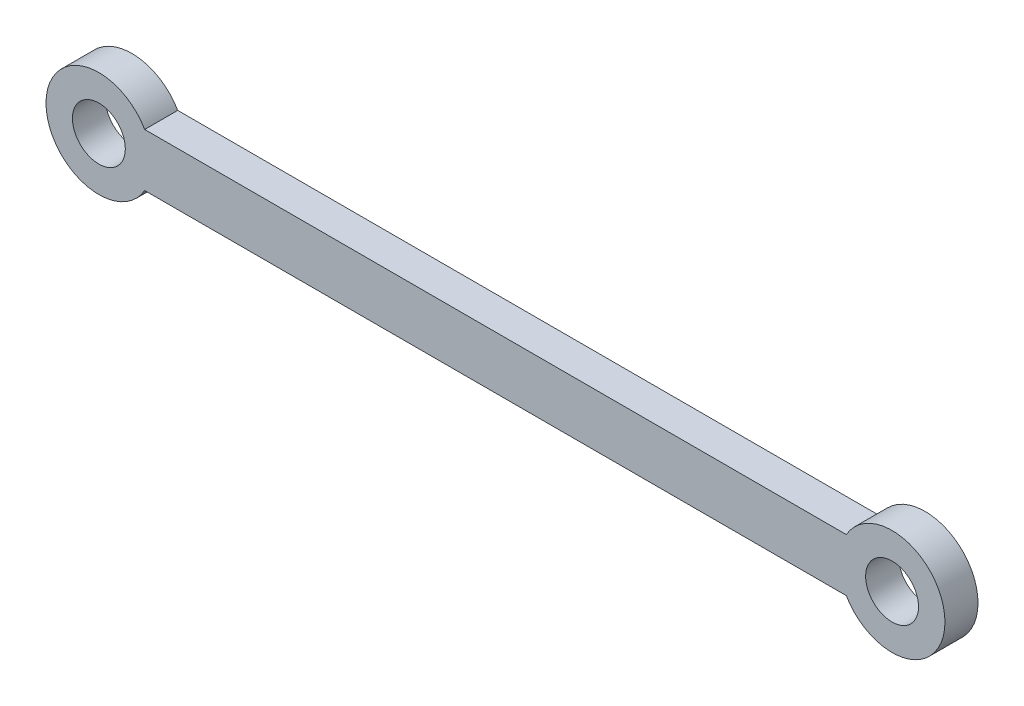
SolidWorks part; units mm, degrees
material "Acrylic (Medium-high impact)"
ref_plane "Front Plane" through (0, 0, 0) normal (0, 0, 1) x (1, 0, 0)
ref_plane "Top Plane" through (0, 0, 0) normal (0, 1, 0) x (1, 0, 0)
ref_plane "Right Plane" through (0, 0, 0) normal (1, 0, 0) x (0, 0, -1)
sketch "Sketch1" plane through (0, 0, 0) normal (0, 0, 1) x (1, 0, 0)
  line L0 (0, 2.54) -> (76.2, 2.54) construction
  line L1 (0, 0) -> (76.2, 0)
  line L2 (0, 0) -> (0, 5.08)
  line L3 (0, 5.08) -> (76.2, 5.08)
  line L4 (76.2, 0) -> (76.2, 5.08)
  line L5 (38.1, 5.08) -> (38.1, 0) construction
  circle A0 centre (0, 2.54) radius 5.08
  circle A1 centre (76.2, 2.54) radius 5.08
  dimension "D3" = 10.16
  dimension "D4" = 10.16
  dimension "D1" = 76.2
  dimension "D2" = 5.08
extrude "Boss-Extrude1" add sketch "Sketch1" along normal blind 3.175
sketch "Sketch2" plane through (0, 0, 3.175) normal (0, 0, 1) x (1, 0, 0)
  line L0 (-5.08, 2.54) -> (81.28, 2.54) construction
  line L1 (0, 7.62) -> (0, -2.54) construction
  line L3 (76.2, 7.62) -> (76.2, -2.54) construction
  arc A0 (4.3994, 5.08) -> (4.3994, 0) centre (0, 2.54) ccw construction
  arc A1 (71.8006, 0) -> (71.8006, 5.08) centre (76.2, 2.54) ccw construction
  circle A4 centre (0, 2.54) radius 2.54
  circle A5 centre (76.2, 2.54) radius 2.54
  dimension "D1" = 5.08
  dimension "D2" = 5.08
extrude "Cut-Extrude1" cut sketch "Sketch2" against normal through all
equation "\"hole-size\"=0.2"
equation "\"D1@Sketch2\"=\"hole-size\""
